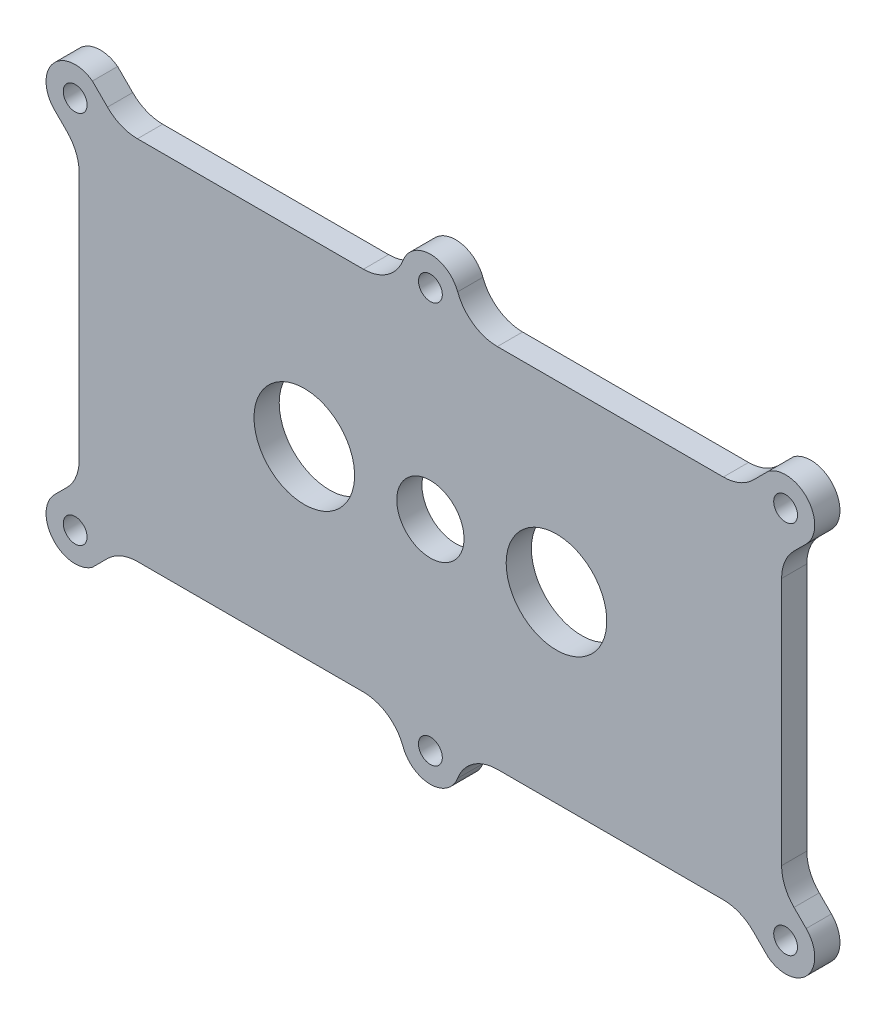
SolidWorks part; units mm, degrees
material "ABS"
ref_plane "X-Y Datum" through (0, 0, 0) normal (0, 0, 1) x (1, 0, 0)
ref_plane "X-Z Datum" through (0, 0, 0) normal (0, 1, 0) x (1, 0, 0)
ref_plane "Y-Z Datum" through (0, 0, 0) normal (1, 0, 0) x (0, 0, -1)
sketch "Sketch1" plane through (0, 0, 0) normal (0, 0, 1) x (1, 0, 0)
  line L14 (66.325, -23.4831) -> (66.325, 23.4831)
  line L15 (70.973, -31.4448) -> (68.6681, -29.14)
  line L16 (60.9798, -36.9181) -> (63.8292, -39.7675)
  line L17 (12.649, -34.575) -> (55.323, -34.575)
  line L18 (-55.323, -34.575) -> (-12.649, -34.575)
  line L19 (-63.8292, -39.7675) -> (-60.9798, -36.9181)
  line L20 (-68.6681, -29.14) -> (-70.973, -31.4448)
  line L21 (-66.325, 23.4831) -> (-66.325, -23.4831)
  line L22 (-70.973, 31.4448) -> (-68.6681, 29.14)
  line L23 (-60.9798, 36.9181) -> (-63.8292, 39.7675)
  line L24 (-12.649, 34.575) -> (-55.323, 34.575)
  line L25 (55.323, 34.575) -> (12.649, 34.575)
  line L26 (63.8292, 39.7675) -> (60.9798, 36.9181)
  line L27 (68.6681, 29.14) -> (70.973, 31.4448)
  line L28 (66.325, -23.4831) -> (66.325, 23.4831)
  line L29 (70.973, -31.4448) -> (68.6681, -29.14)
  line L30 (60.9798, -36.9181) -> (63.8292, -39.7675)
  line L31 (12.649, -34.575) -> (55.323, -34.575)
  line L32 (-55.323, -34.575) -> (-12.649, -34.575)
  line L33 (-63.8292, -39.7675) -> (-60.9798, -36.9181)
  line L34 (-68.6681, -29.14) -> (-70.973, -31.4448)
  line L35 (-66.325, 23.4831) -> (-66.325, -23.4831)
  line L36 (-70.973, 31.4448) -> (-68.6681, 29.14)
  line L37 (-60.9798, 36.9181) -> (-63.8292, 39.7675)
  line L38 (-12.649, 34.575) -> (-55.323, 34.575)
  line L39 (55.323, 34.575) -> (12.649, 34.575)
  line L40 (63.8292, 39.7675) -> (60.9798, 36.9181)
  line L41 (68.6681, 29.14) -> (70.973, 31.4448)
  arc A18 (66.325, -23.4831) -> (68.6681, -29.14) centre (74.325, -23.4831) ccw
  arc A19 (63.8292, -39.7675) -> (70.973, -31.4448) centre (67.0839, -35.3339) ccw
  arc A20 (60.9798, -36.9181) -> (55.323, -34.575) centre (55.323, -42.575) ccw
  arc A21 (12.649, -34.575) -> (5.1533, -39.7796) centre (12.649, -42.575) ccw
  arc A22 (-5.1533, -39.7796) -> (5.1533, -39.7796) centre (0, -37.8577) ccw
  arc A23 (-5.1533, -39.7796) -> (-12.649, -34.575) centre (-12.649, -42.575) ccw
  arc A24 (-55.323, -34.575) -> (-60.9798, -36.9181) centre (-55.323, -42.575) ccw
  arc A25 (-70.973, -31.4448) -> (-63.8292, -39.7675) centre (-67.0839, -35.3339) ccw
  arc A26 (-68.6681, -29.14) -> (-66.325, -23.4831) centre (-74.325, -23.4831) ccw
  arc A27 (-66.325, 23.4831) -> (-68.6681, 29.14) centre (-74.325, 23.4831) ccw
  arc A28 (-63.8292, 39.7675) -> (-70.973, 31.4448) centre (-67.0839, 35.3339) ccw
  arc A29 (-60.9798, 36.9181) -> (-55.323, 34.575) centre (-55.323, 42.575) ccw
  arc A30 (-12.649, 34.575) -> (-5.1533, 39.7796) centre (-12.649, 42.575) ccw
  arc A31 (5.1533, 39.7796) -> (-5.1533, 39.7796) centre (0, 37.8577) ccw
  arc A32 (5.1533, 39.7796) -> (12.649, 34.575) centre (12.649, 42.575) ccw
  arc A33 (55.323, 34.575) -> (60.9798, 36.9181) centre (55.323, 42.575) ccw
  arc A34 (70.973, 31.4448) -> (63.8292, 39.7675) centre (67.0839, 35.3339) ccw
  arc A35 (68.6681, 29.14) -> (66.325, 23.4831) centre (74.325, 23.4831) ccw
  arc A36 (66.325, -23.4831) -> (68.6681, -29.14) centre (74.325, -23.4831) ccw
  arc A37 (63.8292, -39.7675) -> (70.973, -31.4448) centre (67.0839, -35.3339) ccw
  arc A38 (60.9798, -36.9181) -> (55.323, -34.575) centre (55.323, -42.575) ccw
  arc A39 (12.649, -34.575) -> (5.1533, -39.7796) centre (12.649, -42.575) ccw
  arc A40 (-5.1533, -39.7796) -> (5.1533, -39.7796) centre (0, -37.8577) ccw
  arc A41 (-5.1533, -39.7796) -> (-12.649, -34.575) centre (-12.649, -42.575) ccw
  arc A42 (-55.323, -34.575) -> (-60.9798, -36.9181) centre (-55.323, -42.575) ccw
  arc A43 (-70.973, -31.4448) -> (-63.8292, -39.7675) centre (-67.0839, -35.3339) ccw
  arc A44 (-68.6681, -29.14) -> (-66.325, -23.4831) centre (-74.325, -23.4831) ccw
  arc A45 (-66.325, 23.4831) -> (-68.6681, 29.14) centre (-74.325, 23.4831) ccw
  arc A46 (-63.8292, 39.7675) -> (-70.973, 31.4448) centre (-67.0839, 35.3339) ccw
  arc A47 (-60.9798, 36.9181) -> (-55.323, 34.575) centre (-55.323, 42.575) ccw
  arc A48 (-12.649, 34.575) -> (-5.1533, 39.7796) centre (-12.649, 42.575) ccw
  arc A49 (5.1533, 39.7796) -> (-5.1533, 39.7796) centre (0, 37.8577) ccw
  arc A50 (5.1533, 39.7796) -> (12.649, 34.575) centre (12.649, 42.575) ccw
  arc A51 (55.323, 34.575) -> (60.9798, 36.9181) centre (55.323, 42.575) ccw
  arc A52 (70.973, 31.4448) -> (63.8292, 39.7675) centre (67.0839, 35.3339) ccw
  arc A53 (68.6681, 29.14) -> (66.325, 23.4831) centre (74.325, 23.4831) ccw
  dimension "D1" = 0
extrude "Boss-Extrude1" add sketch "Sketch1" against normal blind 4.7625 contours A53 L41 A52 L40 A51 L39 A50 A49 A48 L38 A47 L37 A46 L36 A45 L35 A44 L34 A43 L33 A42 L32 A41 A40 A39 L31 A38 L30 A37 L29 A36 L28
sketch "Sketch2" plane through (0, 0, -4.7625) normal (0, 0, -1) x (-1, 0, 0)
  point P0 (-67.0839, -35.3339)
  point P1 (-67.0839, 35.3339)
  point P3 (0, 37.8577)
  point P5 (67.0839, 35.3339)
  point P7 (67.0839, -35.3339)
  point P9 (0, -37.8577)
hole_wizard "M4 Clearance Hole1" positions "Sketch2" profile "Sketch3" hole size "M4" standard "ANSI Metric" end condition through all
sketch "Sketch3" plane through (67.0839, -35.3339, -4.7625) normal (1, 0, 0) x (0, 1, 0)
  line L0 (0, 0) -> (0, 4.7625)
  line L1 (0, 4.7625) -> (2.25, 4.7625)
  line L2 (2.25, 4.7625) -> (2.25, 0)
  line L5 (2.25, 0) -> (0, 0)
  line L11 (0, -6.35) -> (0, 107.95) construction
  dimension "Thru Hole Dia." = 4.5
  dimension "Thru Hole Depth" = 4.7625
sketch "Sketch4" plane through (0, 0, -4.7625) normal (0, 0, -1) x (-1, 0, 0)
  line L0 (-66.325, 0) -> (66.325, 0) construction
  line L1 (-66.325, -23.4831) -> (-66.325, 23.4831) construction
  line L2 (66.325, 23.4831) -> (66.325, -23.4831) construction
  line L3 (-23.8125, 0) -> (23.8125, 0) construction
  circle A0 centre (0, 0) radius 6.35
  circle A1 centre (-23.8125, 0) radius 9.5
  circle A2 centre (23.8125, 0) radius 9.5
  circle A3 centre (23.8125, 0) radius 12.5 construction
  circle A4 centre (0, 0) radius 9.271 construction
  circle A5 centre (-23.8125, 0) radius 12.5 construction
  point P12 (0, 0)
  dimension "D2" = 19
  dimension "D3" = 25
  dimension "D4" = 12.7
  dimension "D5" = 18.542
  dimension "D1" = 47.625
extrude "Cut-Extrude1" cut sketch "Sketch4" against normal through all
